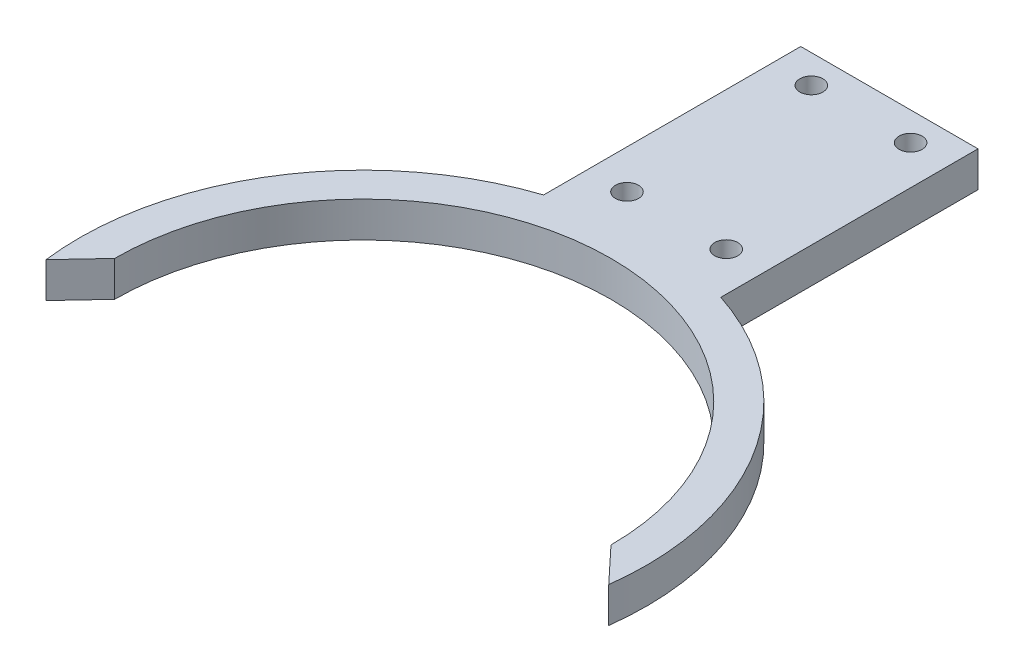
SolidWorks part; units mm, degrees
ref_plane "Alzado" through (0, 0, 0) normal (0, 0, 1) x (1, 0, 0)
ref_plane "Planta" through (0, 0, 0) normal (0, 1, 0) x (1, 0, 0)
ref_plane "Vista lateral" through (0, 0, 0) normal (1, 0, 0) x (0, 0, -1)
sketch "Sketch1" plane through (0, 0, 0) normal (0, 1, 0) x (1, 0, 0)
  line L0 (2.5, 0) -> (2.5, -22.4419) construction
  line L2 (15, 40) -> (-10, 40)
  line L3 (-10, 40) -> (-10, 3.7298)
  line L4 (-32.5, -34.2669) -> (-37.1863, -39.2669)
  line L5 (15, 40) -> (15, 3.7298)
  line L6 (37.5, -34.2669) -> (42.1863, -39.2669)
  arc A0 (37.5, -34.2669) -> (-32.5, -34.2669) centre (2.5, -34.2669) ccw
  arc A1 (-10, 3.7298) -> (-37.1863, -39.2669) centre (2.5, -34.2669) ccw
  arc A2 (15, 3.7298) -> (42.1863, -39.2669) centre (2.5, -34.2669) cw
  circle A3 centre (-4.5, 9.9922) radius 1.625
  circle A4 centre (-4.5, 35.9922) radius 1.625
  circle A5 centre (9.5, 35.9922) radius 1.625
  circle A6 centre (9.5, 9.9922) radius 1.625
  dimension "D1" = 35
  dimension "D4" = 40
  dimension "D5" = 3.25
  dimension "D6" = 3.25
  dimension "D2" = 5.5
  dimension "D3" = 12.5
  dimension "D7" = 26
  dimension "D8" = 7
extrude "Boss-Extrude1" add sketch "Sketch1" along normal blind 5
